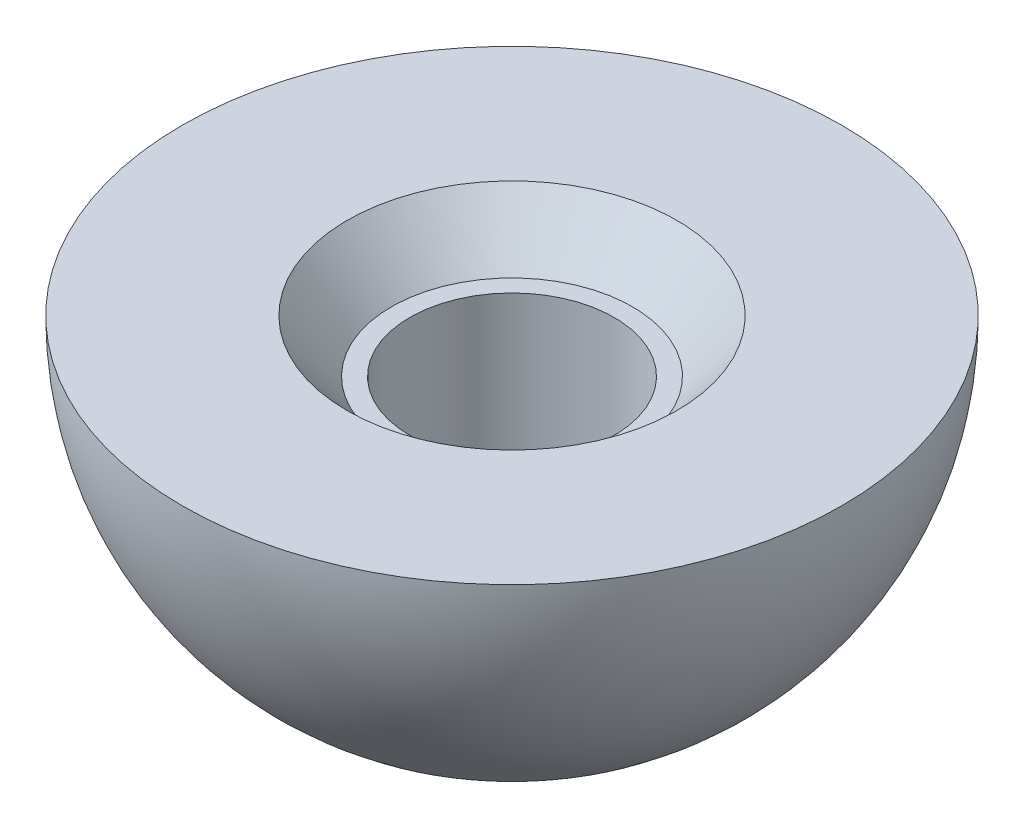
SolidWorks part; units mm, degrees
ref_plane "Front" through (0, 0, 0) normal (0, 0, 1) x (1, 0, 0)
ref_plane "Top" through (0, 0, 0) normal (0, 1, 0) x (1, 0, 0)
ref_plane "Right" through (0, 0, 0) normal (1, 0, 0) x (0, 0, -1)
sketch "Sketch1" plane through (0, 0, 0) normal (0, 1, 0) x (1, 0, 0)
  line L0 (5, 0) -> (-5, 0)
  arc A0 (5, 0) -> (-5, 0) centre (0, 0) ccw
  dimension "D1" = 10
revolve "Revolve1" add sketch "Sketch1" angle 180 about L0
sketch "Sketch2" plane through (0, 0, 0) normal (0, 1, 0) x (1, 0, 0)
  circle A0 centre (0, 0) radius 1.55
  dimension "D1" = 3.1
extrude "Cut-Extrude1" cut sketch "Sketch2" against normal through all
sketch "Sketch3" plane through (0, 0, 0) normal (0, 1, 0) x (1, 0, 0)
  circle A0 centre (0, 0) radius 2.5
  dimension "D1" = 5
extrude "Cut-Extrude2" cut sketch "Sketch3" against normal blind 0.8 draft 40
